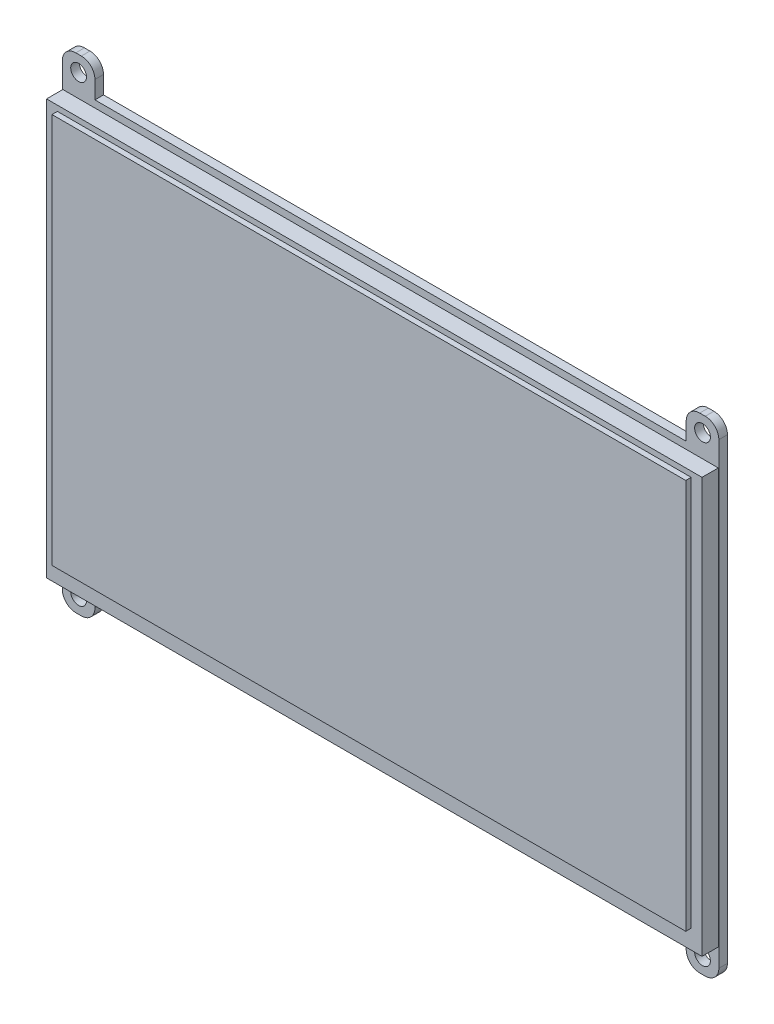
SolidWorks part; units mm, degrees
ref_plane "Front Plane" through (0, 0, 0) normal (0, 0, 1) x (1, 0, 0)
ref_plane "Top Plane" through (0, 0, 0) normal (0, 1, 0) x (1, 0, 0)
ref_plane "Right Plane" through (0, 0, 0) normal (1, 0, 0) x (0, 0, -1)
sketch "Sketch1" plane through (0, 0, 0) normal (0, 0, 1) x (1, 0, 0)
  line L0 (-60.555, 0) -> (60.555, 0) construction
  line L1 (-60.555, 38.965) -> (60.555, 38.965)
  line L2 (-60.555, 38.965) -> (-60.555, -38.965)
  line L3 (-60.555, -38.965) -> (60.555, -38.965)
  line L4 (60.555, 38.965) -> (60.555, -38.965)
  line L5 (-60.555, 38.965) -> (60.555, -38.965) construction
  line L6 (-60.555, -38.965) -> (60.555, 38.965) construction
  line L7 (0, 0) -> (0, 38.965) construction
  line L8 (-57.545, 44.725) -> (-57.545, 38.965) construction
  line L9 (-60.555, 38.965) -> (-60.555, 42.225)
  line L10 (-58.055, 44.725) -> (-57.035, 44.725)
  line L11 (-54.535, 38.965) -> (-54.535, 42.225)
  line L12 (57.545, 44.725) -> (57.545, 38.965) construction
  line L13 (54.535, 38.965) -> (54.535, 42.225)
  line L14 (58.055, 44.725) -> (57.035, 44.725)
  line L15 (60.555, 38.965) -> (60.555, 42.225)
  line L16 (57.545, -44.725) -> (57.545, -38.965) construction
  line L17 (-57.545, -44.725) -> (-57.545, -38.965) construction
  line L18 (60.555, -38.965) -> (60.555, -42.225)
  line L19 (58.055, -44.725) -> (57.035, -44.725)
  line L20 (54.535, -38.965) -> (54.535, -42.225)
  line L21 (-54.535, -38.965) -> (-54.535, -42.225)
  line L22 (-58.055, -44.725) -> (-57.035, -44.725)
  line L23 (-60.555, -38.965) -> (-60.555, -42.225)
  arc A0 (-57.035, 44.725) -> (-54.535, 42.225) centre (-57.035, 42.225) cw
  arc A1 (-58.055, 44.725) -> (-60.555, 42.225) centre (-58.055, 42.225) ccw
  circle A2 centre (-57.545, 41.845) radius 1.4544
  circle A3 centre (57.545, 41.845) radius 1.4544
  arc A4 (58.055, 44.725) -> (60.555, 42.225) centre (58.055, 42.225) cw
  arc A5 (57.035, 44.725) -> (54.535, 42.225) centre (57.035, 42.225) ccw
  arc A6 (57.035, -44.725) -> (54.535, -42.225) centre (57.035, -42.225) cw
  arc A7 (58.055, -44.725) -> (60.555, -42.225) centre (58.055, -42.225) ccw
  circle A8 centre (57.545, -41.845) radius 1.4544
  circle A9 centre (-57.545, -41.845) radius 1.4544
  arc A10 (-58.055, -44.725) -> (-60.555, -42.225) centre (-58.055, -42.225) cw
  arc A11 (-57.035, -44.725) -> (-54.535, -42.225) centre (-57.035, -42.225) ccw
  point P0 (0, 0)
  dimension "D5" = 2.5
  dimension "D1" = 121.11
  dimension "D2" = 77.93
  dimension "D3" = 89.45
  dimension "D4" = 109.07
extrude "Boss-Extrude1" add sketch "Sketch1" along normal blind 1.5875 contours L4 L1 L2 L3 | L14 A5 L13 L1 L15 A4 A3 | L19 A7 L18 L3 L20 A6 A8 | L10 A1 L9 L1 L11 A0 A2 | L22 A11 L21 L3 L23 A10 A9
sketch "Sketch2" plane through (0, 0, 1.5875) normal (0, 0, 1) x (1, 0, 0)
  line L1 (-60.455, 37.6642) -> (60.455, 37.6642)
  line L2 (-60.455, 37.6642) -> (-60.455, -38.865)
  line L3 (-60.455, -38.865) -> (60.455, -38.865)
  line L4 (60.455, 37.6642) -> (60.455, -38.865)
  line L7 (-60.555, 42.225) -> (-60.555, -42.225) construction
  line L8 (-54.535, -38.965) -> (54.535, -38.965) construction
  line L10 (60.555, 42.225) -> (60.555, -42.225) construction
  dimension "D1" = 0.1
  dimension "D2" = 0.1
  dimension "D3" = 0.1
extrude "Boss-Extrude2" add sketch "Sketch2" along normal blind 3
sketch "Sketch3" plane through (0, 0, 4.5875) normal (0, 0, 1) x (1, 0, 0)
  line L0 (-60.455, 37.6642) -> (-60.455, -38.865) construction
  line L1 (-58.455, 36.6642) -> (58.455, 36.6642)
  line L2 (-58.455, 36.6642) -> (-58.455, -35.365)
  line L3 (-58.455, -35.365) -> (58.455, -35.365)
  line L4 (58.455, 36.6642) -> (58.455, -35.365)
  line L5 (60.455, -38.865) -> (60.455, 37.6642) construction
  line L6 (-60.455, -38.865) -> (60.455, -38.865) construction
  line L7 (60.455, 37.6642) -> (-60.455, 37.6642) construction
  dimension "D1" = 2
  dimension "D2" = 2
  dimension "D3" = 3.5
  dimension "D4" = 1
extrude "Boss-Extrude3" add sketch "Sketch3" along normal blind 1
